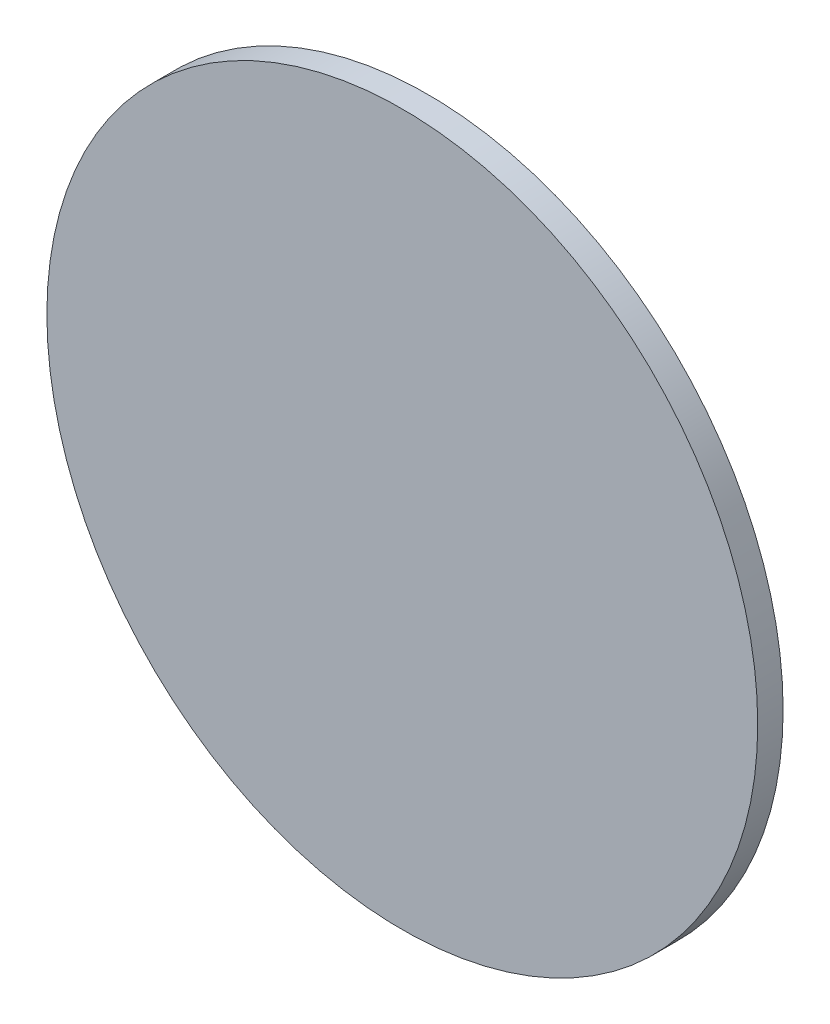
SolidWorks part; units mm, degrees
ref_plane "Front Plane" through (0, 0, 0) normal (0, 0, 1) x (1, 0, 0)
ref_plane "Top Plane" through (0, 0, 0) normal (0, 1, 0) x (1, 0, 0)
ref_plane "Right Plane" through (0, 0, 0) normal (1, 0, 0) x (0, 0, -1)
sketch "Sketch1" plane through (0, 0, 0) normal (0, 0, 1) x (1, 0, 0)
  circle A0 centre (0, 0) radius 140
  dimension "D1" = 280
extrude "Boss-Extrude1" add sketch "Sketch1" along normal blind 10
sketch "holePoints" plane through (0, 0, 0) normal (0, 0, -1) x (-1, 0, 0)
  point P0 (-80.3278, 46.343)
  point P1 (-14.8298, 70.2353)
  point P2 (65.91, 62.4085)
  point P3 (84.0353, 9.6805)
  point P4 (74.9726, -53.7578)
  point P5 (-4.1194, -77.2383)
  point P6 (-53.9638, -40.9878)
